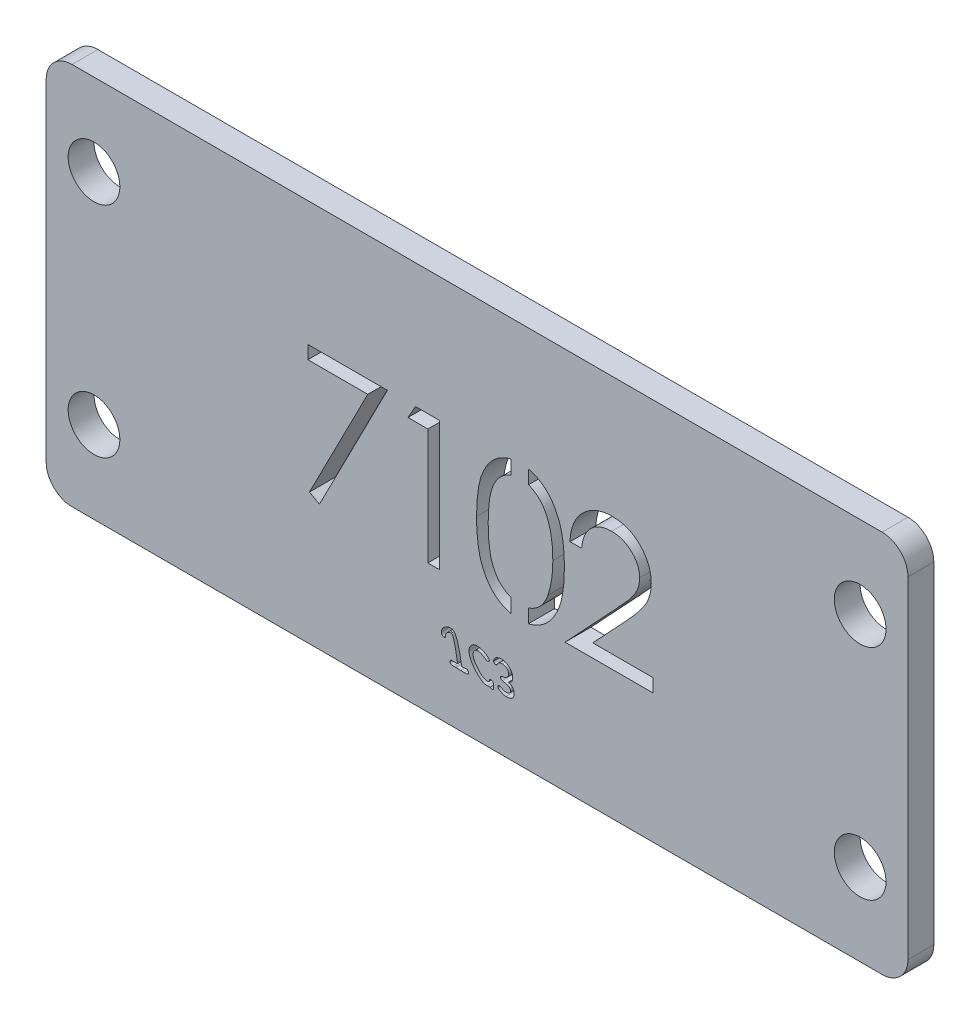
SolidWorks part; units mm, degrees
ref_plane "Front Plane" through (0, 0, 0) normal (0, 0, 1) x (1, 0, 0)
ref_plane "Top Plane" through (0, 0, 0) normal (0, 1, 0) x (1, 0, 0)
ref_plane "Right Plane" through (0, 0, 0) normal (1, 0, 0) x (0, 0, -1)
sketch "Sketch1" plane through (0, 0, 0) normal (0, 0, 1) x (1, 0, 0)
  line L0 (-50.8, 60.0297) -> (-50.8, -22.9634) construction
  line L1 (-50, 22.225) -> (50, 22.225)
  line L2 (-50, 22.225) -> (-50, -22.225)
  line L3 (-50, -22.225) -> (50, -22.225)
  line L4 (50, 22.225) -> (50, -22.225)
  line L5 (-50, 22.225) -> (50, -22.225) construction
  line L6 (-50, -22.225) -> (50, 22.225) construction
  line L7 (0, 25.4) -> (-17.9869, 25.4) construction
  line L8 (-44.45, 12.7) -> (44.45, 12.7) construction
  line L9 (-44.45, 12.7) -> (-44.45, -12.7) construction
  line L10 (-44.45, -12.7) -> (44.45, -12.7) construction
  line L11 (44.45, 12.7) -> (44.45, -12.7) construction
  line L12 (-44.45, 12.7) -> (44.45, -12.7) construction
  line L13 (-44.45, -12.7) -> (44.45, 12.7) construction
  line L14 (52.8, 0) -> (-52.8, 0) construction
  line L15 (0, -25.4) -> (-17.9869, -25.4) construction
  line L16 (-35.6669, 22.86) -> (-39.2133, 22.86) construction
  circle A0 centre (-44.45, 12.7) radius 3
  circle A1 centre (-44.45, -12.7) radius 3
  circle A2 centre (44.45, 12.7) radius 3
  circle A3 centre (44.45, -12.7) radius 3
  point P0 (0, 0)
  point P7 (0, 0)
  dimension "D8" = 6
  dimension "D1" = 6.35
  dimension "D2" = 100
  dimension "D3" = 44.45
  dimension "D4" = 88.9
  dimension "D5" = 25.4
  dimension "D6" = 25.4
  dimension "D7" = 2.54
extrude "Boss-Extrude1" add sketch "Sketch1" along normal mid plane 3 contours A0
fillet "Fillet1" radius 3 4 edges at (50, -22.225, 0) (-50, -22.225, 0) (-50, 22.225, 0) (50, 22.225, 0)
sketch "Sketch2" plane through (0, 0, 1.5) normal (0, 0, 1) x (1, 0, 0)
  line L0 (-50, -7.225) -> (50, -7.225) construction
  line L1 (-50, 19.225) -> (-50, -19.225) construction
  line L2 (50, -19.225) -> (50, 19.225) construction
  line L3 (-47, -22.225) -> (47, -22.225) construction
  text T0 "7102" font "Century Gothic" height 15
  dimension "D1" = 15
extrude "Cut-Extrude1" cut sketch "Sketch2" against normal through all both and the other way through all
sketch "Sketch3" plane through (0, 0, 1.5) normal (0, 0, 1) x (1, 0, 0)
  line L0 (4.9573, 8.1596) -> (4.9573, -7.6096) construction
  line L1 (3.9573, 8.0504) -> (3.9573, -7.5003)
  line L2 (5.9573, 8.0537) -> (5.9573, -7.5011)
  line L3 (3.9573, -7.5003) -> (3.9573, -7.6096) construction
  line L4 (3.9573, 8.1596) -> (3.9573, -7.6096) construction
  line L5 (5.9573, -7.5011) -> (5.9573, -7.6096) construction
  line L6 (5.9573, 8.1596) -> (5.9573, -7.6096) construction
  line L7 (3.9573, 8.1596) -> (3.9573, 8.0504) construction
  line L8 (5.9573, 8.1596) -> (5.9573, 8.0537) construction
  spline S0 degree 3 poles (3.9573, 8.0504) (3.9461, 8.0478) (3.8244, 8.019) (3.5945, 7.9525) (3.2728, 7.8372) (2.961, 7.6907) (2.6583, 7.5191) (2.3625, 7.3243) (2.0821, 7.1021) (1.8146, 6.8582) (1.569, 6.5854) (1.3358, 6.2901) (1.1216, 5.9681) (0.9178, 5.6247) (0.7359, 5.2543) (0.5688, 4.8575) (0.4207, 4.427) (0.293, 3.9571) (0.1806, 3.4461) (0.0964, 2.8917) (0.0273, 2.2953) (-0.0232, 1.6569) (-0.0536, 0.9764) (-0.0563, 0.5094) (-0.0577, 0.269) knots 0.095865 0.095865 0.095865 0.095865 0.099153 0.13154 0.164087 0.196563 0.229707 0.263315 0.297504 0.331686 0.366482 0.4021 0.438958 0.476748 0.515985 0.556589 0.599519 0.645765 0.695487 0.748721 0.805687 0.866754 0.931405 1 1 1 1 construction
  spline S1 degree 3 poles (10.1346, 0.269) (10.1319, 0.4994) (10.1265, 0.9483) (10.0979, 1.605) (10.0437, 2.2254) (9.9694, 2.81) (9.8734, 3.3576) (9.7582, 3.87) (9.6157, 4.3447) (9.4576, 4.7873) (9.2744, 5.1952) (9.0843, 5.5798) (8.8718, 5.9346) (8.6487, 6.2658) (8.4058, 6.5677) (8.15, 6.846) (7.8781, 7.0979) (7.59, 7.3206) (7.2929, 7.5205) (6.9835, 7.6905) (6.6666, 7.8366) (6.3403, 7.9532) (6.1023, 8.0203) (5.9736, 8.05) (5.9573, 8.0537) knots 0 0 0 0 0.065278 0.127205 0.186168 0.241675 0.294115 0.343609 0.390387 0.434463 0.476646 0.517002 0.555936 0.593716 0.630057 0.665601 0.700745 0.734917 0.768681 0.802087 0.834849 0.867433 0.900138 0.904855 0.904855 0.904855 0.904855 construction
  spline S2 degree 3 poles (5.9573, -7.5011) (5.9746, -7.4973) (6.1044, -7.468) (6.3441, -7.4011) (6.6694, -7.2788) (6.9899, -7.1364) (7.2983, -6.9597) (7.6001, -6.7622) (7.889, -6.5366) (8.1619, -6.283) (8.4221, -6.0066) (8.6623, -5.7007) (8.8877, -5.3707) (9.0946, -5.0142) (9.2877, -4.6342) (9.4651, -4.2273) (9.6273, -3.7891) (9.7587, -3.3137) (9.877, -2.8048) (9.9732, -2.2602) (10.0427, -1.6782) (10.0982, -1.0611) (10.1264, -0.4074) (10.1318, 0.0396) (10.1346, 0.269) knots 0.095271 0.095271 0.095271 0.095271 0.10028 0.133019 0.165736 0.198792 0.232372 0.266409 0.301016 0.336196 0.371972 0.408574 0.446394 0.485225 0.525372 0.567224 0.611081 0.65775 0.70702 0.759235 0.814484 0.873227 0.934937 1 1 1 1 construction
  spline S3 degree 3 poles (-0.0577, 0.269) (-0.0563, 0.0306) (-0.0536, -0.4334) (-0.023, -1.1099) (0.0266, -1.7455) (0.0991, -2.3398) (0.189, -2.8932) (0.2941, -3.408) (0.4271, -3.88) (0.5778, -4.3136) (0.7477, -4.7135) (0.9335, -5.0857) (1.1345, -5.4325) (1.353, -5.7526) (1.5828, -6.0504) (1.8298, -6.3231) (2.0959, -6.5663) (2.3745, -6.7863) (2.6672, -6.9783) (2.9685, -7.1468) (3.2774, -7.2932) (3.5976, -7.4056) (3.8256, -7.4695) (3.9461, -7.4977) (3.9573, -7.5003) knots 0 0 0 0 0.068113 0.132564 0.193427 0.250218 0.303569 0.353576 0.400235 0.443586 0.484619 0.524292 0.56238 0.599049 0.63494 0.669782 0.704009 0.737842 0.771098 0.803896 0.836415 0.868639 0.900715 0.904006 0.904006 0.904006 0.904006 construction
  spline S4 degree 3 poles (290.7165, -4998.7854) (-19.971, 47.4278) (-5.3683, -8.9824) (5.6653, -7.5591) (6.0093, -7.4945) (6.3441, -7.4011) (6.6694, -7.2788) (6.9899, -7.1364) (7.2983, -6.9597) (7.6001, -6.7622) (7.889, -6.5366) (8.1619, -6.283) (8.4221, -6.0066) (8.6623, -5.7007) (8.8877, -5.3707) (9.0946, -5.0142) (9.2877, -4.6342) (9.4651, -4.2273) (9.6273, -3.7891) (9.7587, -3.3137) (9.877, -2.8048) (9.9732, -2.2602) (10.0427, -1.6782) (10.0982, -1.0611) (11.2253, 25.0712) (-34.2237, 51.8093) (5009.343, -10.5031) knots -3.049857 -3.049857 -3.049857 -3.049857 0.033824 0.067298 0.10028 0.133019 0.165736 0.198792 0.232372 0.266409 0.301016 0.336196 0.371972 0.408574 0.446394 0.485225 0.525372 0.567224 0.611081 0.65775 0.70702 0.759235 0.814484 0.873227 0.934937 8.230597 8.230597 8.230597 8.230597 only from (4.9573, -7.6096) to (10.1346, 0.269)
  spline S5 degree 3 poles (-4999.1582, -34.1053) (49.0413, 49.3538) (-1.1445, 23.6805) (-0.023, -1.1099) (0.0266, -1.7455) (0.0991, -2.3398) (0.189, -2.8932) (0.2941, -3.408) (0.4271, -3.88) (0.5778, -4.3136) (0.7477, -4.7135) (0.9335, -5.0857) (1.1345, -5.4325) (1.353, -5.7526) (1.5828, -6.0504) (1.8298, -6.3231) (2.0959, -6.5663) (2.3745, -6.7863) (2.6672, -6.9783) (2.9685, -7.1468) (3.2774, -7.2932) (3.5976, -7.4056) (3.9246, -7.4974) (4.2601, -7.5629) (15.6551, -8.9071) (30.0889, 45.1647) (-245.78, -5000.6104) knots -6.894924 -6.894924 -6.894924 -6.894924 0.068113 0.132564 0.193427 0.250218 0.303569 0.353576 0.400235 0.443586 0.484619 0.524292 0.56238 0.599049 0.63494 0.669782 0.704009 0.737842 0.771098 0.803896 0.836415 0.868639 0.900715 0.933378 0.966213 4.173797 4.173797 4.173797 4.173797 only from (-0.0577, 0.269) to (4.9573, -7.6096)
  spline S6 degree 3 poles (-252.1523, 5001.0547) (30.1159, -44.7299) (15.6301, 9.4602) (4.2601, 8.1128) (3.9233, 8.0477) (3.5945, 7.9525) (3.2728, 7.8372) (2.961, 7.6907) (2.6583, 7.5191) (2.3625, 7.3243) (2.0821, 7.1021) (1.8146, 6.8582) (1.569, 6.5854) (1.3358, 6.2901) (1.1216, 5.9681) (0.9178, 5.6247) (0.7359, 5.2543) (0.5688, 4.8575) (0.4207, 4.427) (0.293, 3.9571) (0.1806, 3.4461) (0.0964, 2.8917) (0.0273, 2.2953) (-0.0232, 1.6569) (-1.1408, -23.3783) (48.9646, -49.249) (-4999.2429, 29.5612) knots -3.162862 -3.162862 -3.162862 -3.162862 0.033742 0.066533 0.099153 0.13154 0.164087 0.196563 0.229707 0.263315 0.297504 0.331686 0.366482 0.4021 0.438958 0.476748 0.515985 0.556589 0.599519 0.645765 0.695487 0.748721 0.805687 0.866754 0.931405 7.95429 7.95429 7.95429 7.95429 only from (4.9573, 8.1596) to (-0.0577, 0.269)
  spline S7 degree 3 poles (5009.2427, 22.5268) (-34.5854, -51.2047) (11.2322, -24.4414) (10.0979, 1.605) (10.0437, 2.2254) (9.9694, 2.81) (9.8734, 3.3576) (9.7582, 3.87) (9.6157, 4.3447) (9.4576, 4.7873) (9.2744, 5.1952) (9.0843, 5.5798) (8.8718, 5.9346) (8.6487, 6.2658) (8.4058, 6.5677) (8.15, 6.846) (7.8781, 7.0979) (7.59, 7.3206) (7.2929, 7.5205) (6.9835, 7.6905) (6.6666, 7.8366) (6.3403, 7.9532) (6.0073, 8.0471) (5.6646, 8.1134) (-6.0099, 9.4435) (-20.5358, -43.7722) (242.397, 5001.9405) knots -7.198197 -7.198197 -7.198197 -7.198197 0.065278 0.127205 0.186168 0.241675 0.294115 0.343609 0.390387 0.434463 0.476646 0.517002 0.555936 0.593716 0.630057 0.665601 0.700745 0.734917 0.768681 0.802087 0.834849 0.867433 0.900138 0.932806 0.966212 4.224046 4.224046 4.224046 4.224046 only from (10.1346, 0.269) to (4.9573, 8.1596)
  spline S8 degree 3 poles (4.9573, -7.6096) (5.0767, -7.6079) (5.3141, -7.6044) (5.6478, -7.5614) (5.861, -7.5223) (5.9573, -7.5011) knots 0 0 0 0 0.033824 0.067298 0.095271 0.095271 0.095271 0.095271
  spline S9 degree 3 poles (3.9573, -7.5003) (4.0575, -7.5233) (4.2716, -7.5643) (4.6058, -7.6037) (4.839, -7.6076) (4.9573, -7.6096) knots 0.904006 0.904006 0.904006 0.904006 0.933378 0.966213 1 1 1 1
  spline S10 degree 3 poles (4.9573, 8.1596) (4.839, 8.1576) (4.6057, 8.1537) (4.2716, 8.1141) (4.0575, 8.0736) (3.9573, 8.0504) knots 0 0 0 0 0.033742 0.066533 0.095865 0.095865 0.095865 0.095865
  spline S11 degree 3 poles (5.9573, 8.0537) (5.8611, 8.0753) (5.648, 8.1153) (5.3139, 8.1534) (5.0766, 8.1575) (4.9573, 8.1596) knots 0.904855 0.904855 0.904855 0.904855 0.932806 0.966212 1 1 1 1
  dimension "D1" = 1
  dimension "D2" = 1
  dimension "D3" = 0
extrude "Boss-Extrude2" add sketch "Sketch3" against normal up to surface (3 mm away) contours L1 S9 S8 L2 S11 S10 up to face at (-5.8853, 2.2622, -1.5)
sketch "Sketch4" plane through (0, 0, 1.5) normal (0, 0, 1) x (1, 0, 0)
  line L0 (-41.45, -12.7) -> (41.45, -12.7) construction
  circle A2 centre (-44.45, -12.7) radius 3 construction
  circle A3 centre (44.45, -12.7) radius 3 construction
  text T0 "JC3\r\n" font "Comic Sans MS" height 3.5
extrude "Cut-Extrude2" cut sketch "Sketch4" against normal through all both and the other way through all
